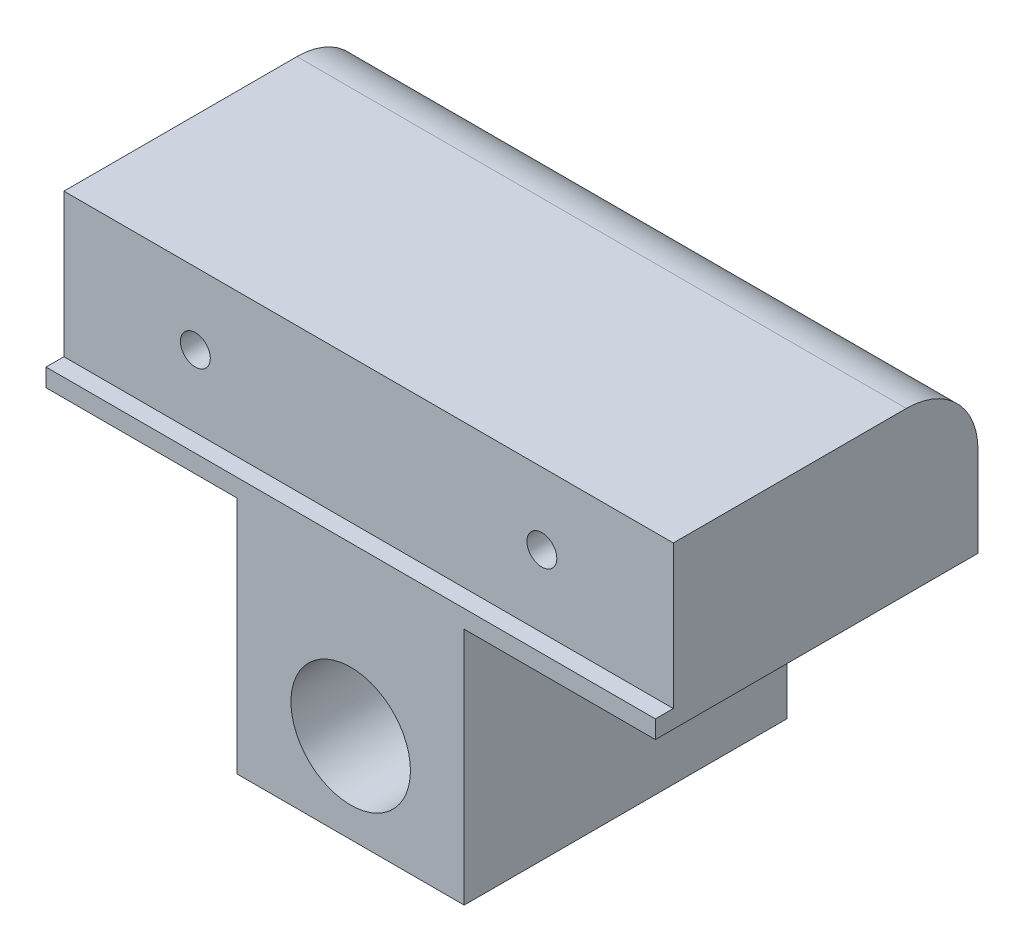
SolidWorks part; units mm, degrees
ref_plane "Front Plane" through (0, 0, 0) normal (0, 0, 1) x (1, 0, 0)
ref_plane "Top Plane" through (0, 0, 0) normal (0, 1, 0) x (1, 0, 0)
ref_plane "Right Plane" through (0, 0, 0) normal (1, 0, 0) x (0, 0, -1)
sketch "Sketch1" plane through (0, 0, 0) normal (1, 0, 0) x (0, 0, -1)
  line L0 (-40.6903, 0) -> (56.6691, 0) construction
  line L1 (-5.361, 52) -> (-5.361, 28)
  line L2 (-5.361, 28) -> (-8.361, 28)
  line L3 (-8.361, 28) -> (-8.361, 25)
  line L4 (-8.361, 25) -> (45.639, 25)
  line L5 (45.639, 25) -> (45.639, 40)
  line L6 (33.639, 52) -> (-5.361, 52)
  arc A0 (45.639, 40) -> (33.639, 52) centre (33.639, 40) ccw
  point P11 (45.639, 52)
  dimension "D5" = 12
  dimension "D1" = 51
  dimension "D2" = 3
  dimension "D3" = 27
  dimension "D4" = 3
  dimension "D6" = 25
extrude "Extrude1" add sketch "Sketch1" along normal blind 102
sketch "Sketch3" plane through (0, 0, 8.361) normal (0, 0, 1) x (1, 0, 0)
  line L0 (51, 52) -> (51, 1.3895) construction
  line L1 (102, 52) -> (0, 52) construction
  line L2 (102, 25) -> (0, 25) construction
  line L3 (32, 25) -> (70, 25)
  line L4 (32, 25) -> (32, -15)
  line L5 (32, -15) -> (70, -15)
  line L6 (70, 25) -> (70, -15)
  dimension "D1" = 40
  dimension "D2" = 38
  dimension "D3" = 19
extrude "Extrude3" add sketch "Sketch3" against normal blind 54
sketch "Sketch4" plane through (0, 0, 8.361) normal (0, 0, 1) x (1, 0, 0)
  line L0 (51, -15) -> (51, 52) construction
  line L1 (32, -15) -> (70, -15) construction
  line L2 (102, 52) -> (0, 52) construction
  circle A0 centre (51, 0) radius 10
  dimension "D2" = 20
  dimension "D1" = 25
extrude "Extrude4" cut sketch "Sketch4" against normal through all
sketch "Sketch5" plane through (0, 0, 5.361) normal (0, 0, 1) x (1, 0, 0)
  point P5 (22, 40)
  point P6 (80, 40)
hole_wizard "M6 Tapped Hole1" positions "3DSketch1" profile "Sketch6" tap size "M6" standard "ISO"
sketch3d "3DSketch1"
  point P0 (22, 40, 5.361)
  point P3 (80, 40, 5.361)
sketch "Sketch6" plane through (22, 40, 5.361) normal (1, 0, 0) x (0, -1, 0)
  line L0 (0, 0) -> (0, 15.5022)
  line L1 (0, 15.5022) -> (2.5, 14)
  line L2 (2.5, 14) -> (2.5, 0)
  line L5 (2.5, 0) -> (0, 0)
  line L10 (0, 15.5022) -> (-2.5, 14) construction
  line L11 (0, -6.35) -> (0, 107.95) construction
  dimension "Tap Drill Dia." = 5
  dimension "Tap Drill Depth" = 14
  dimension "Drill Angle" = 118
cosmetic thread "Hole Thread1" parameters "D1"=12, "D2"=6
cosmetic thread "Hole Thread2" parameters "D1"=12, "D2"=6
sketch "Sketch7" plane through (0, -15, 0) normal (0, -1, 0) x (1, 0, 0)
  line L0 (32, -18.639) -> (70, -18.639) construction
  line L1 (32, -45.639) -> (32, 8.361) construction
  line L2 (70, -45.639) -> (70, 8.361) construction
  line L3 (51, 8.361) -> (51, -45.639) construction
  line L4 (32, 8.361) -> (70, 8.361) construction
  line L5 (32, -45.639) -> (70, -45.639) construction
  point P12 (39, -18.639)
  point P13 (63, -18.639)
  dimension "D1" = 24
  dimension "D2" = 12
hole_wizard "M6 Tapped Hole2" positions "3DSketch2" profile "Sketch8" tap size "M6" standard "ISO"
sketch3d "3DSketch2"
  point P0 (39, -15, -18.639)
  point P3 (63, -15, -18.639)
sketch "Sketch8" plane through (39, -15, -18.639) normal (1, 0, 0) x (0, 0, -1)
  line L0 (0, 0) -> (0, 11.5022)
  line L1 (0, 11.5022) -> (2.5, 10)
  line L2 (2.5, 10) -> (2.5, 0)
  line L5 (2.5, 0) -> (0, 0)
  line L10 (0, 11.5022) -> (-2.5, 10) construction
  line L11 (0, -6.35) -> (0, 107.95) construction
  dimension "Tap Drill Dia." = 5
  dimension "Tap Drill Depth" = 10
  dimension "Drill Angle" = 118
cosmetic thread "Hole Thread3" parameters "D1"=8, "D2"=6
cosmetic thread "Hole Thread4" parameters "D1"=8, "D2"=6
